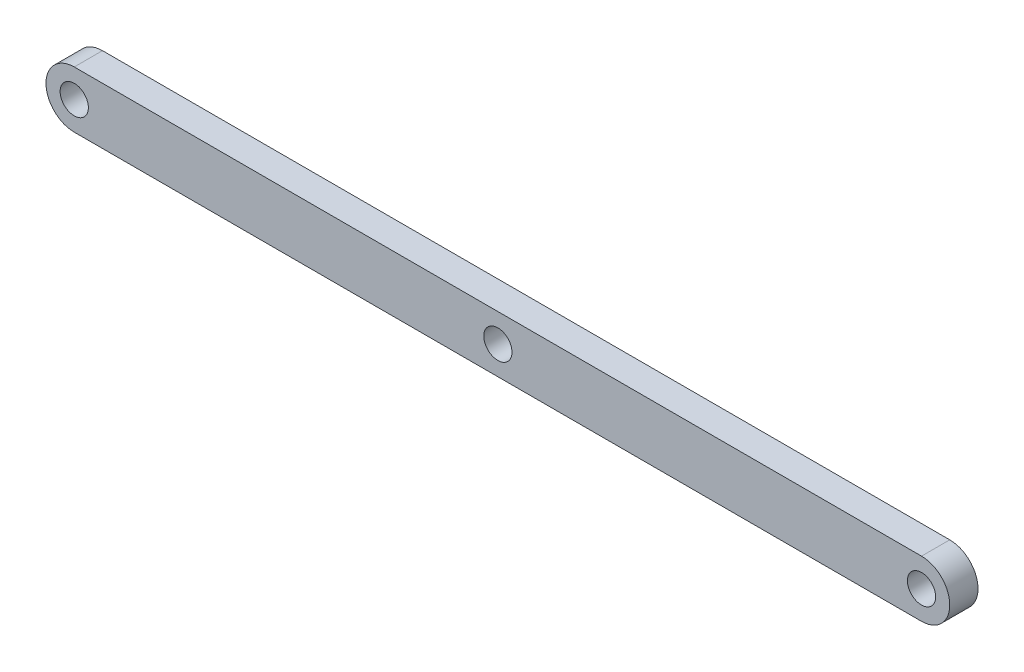
SolidWorks part; units mm, degrees
ref_plane "Front Plane" through (0, 0, 0) normal (0, 0, 1) x (1, 0, 0)
ref_plane "Top Plane" through (0, 0, 0) normal (0, 1, 0) x (1, 0, 0)
ref_plane "Right Plane" through (0, 0, 0) normal (1, 0, 0) x (0, 0, -1)
sketch "Sketch1" plane through (0, 0, 0) normal (0, 0, 1) x (1, 0, 0)
  line L0 (0, 0) -> (300, 0) construction
  line L1 (0, 10) -> (300, 10)
  line L2 (0, -10) -> (300, -10)
  arc A0 (0, 10) -> (0, -10) centre (0, 0) ccw
  arc A1 (300, -10) -> (300, 10) centre (300, 0) ccw
  circle A2 centre (0, 0) radius 5
  circle A3 centre (300, 0) radius 5
  circle A4 centre (150, 0) radius 5
  point P3 (150, 0)
  dimension "D2" = 10
  dimension "D1" = 300
  dimension "D3" = 20
extrude "Boss-Extrude1" add sketch "Sketch1" along normal blind 10
